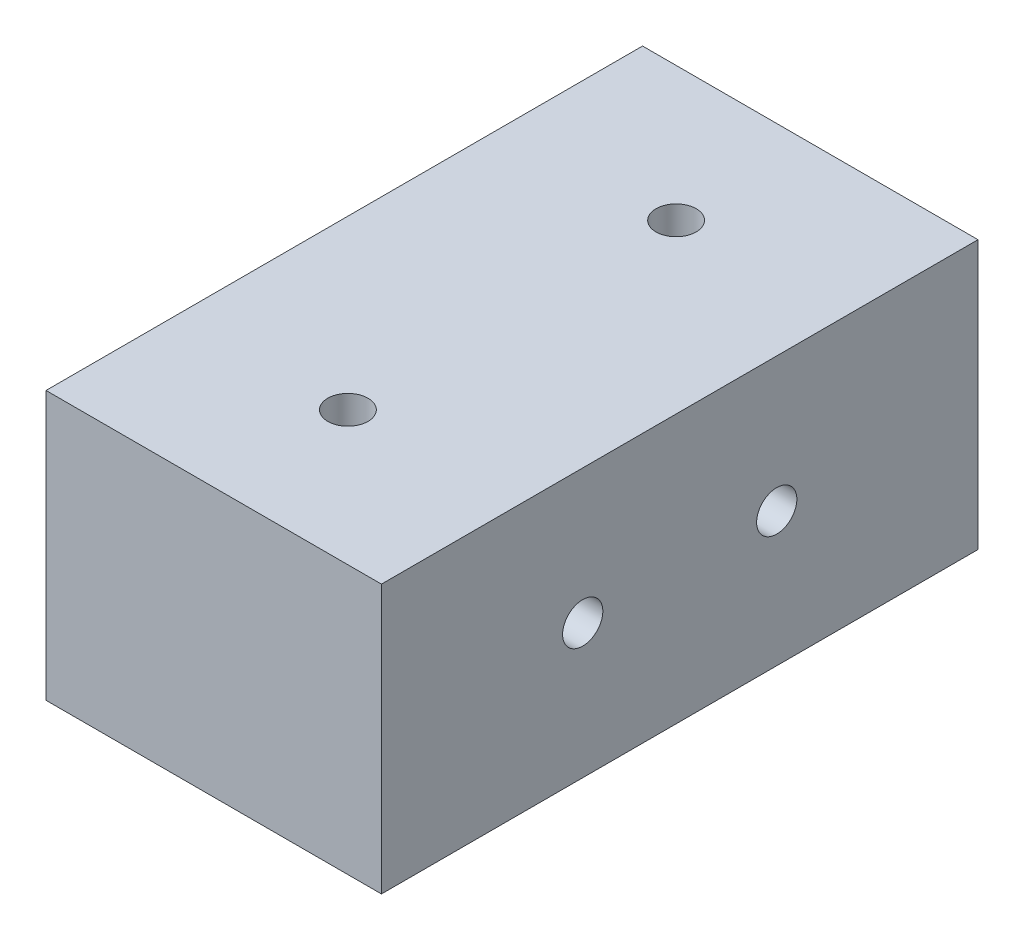
SolidWorks part; units mm, degrees
ref_plane "Alzado" through (0, 0, 0) normal (0, 0, 1) x (1, 0, 0)
ref_plane "Planta" through (0, 0, 0) normal (0, 1, 0) x (1, 0, 0)
ref_plane "Vista lateral" through (0, 0, 0) normal (1, 0, 0) x (0, 0, -1)
sketch "Croquis2" plane through (0, 0, 0) normal (1, 0, 0) x (0, 0, -1)
  line L0 (0, 0) -> (-44.4603, 0)
  line L1 (0, 0) -> (-50, 0) construction
  line L3 (0, -20) -> (-44.4603, -20)
  line L7 (0, -20) -> (0, 0)
  line L8 (-44.4603, -20) -> (-44.4603, 0)
  line L10 (-50, 0) -> (-75.7248, -15.4349) construction
  line L11 (-44.4603, -20) -> (-55.7248, -26.7587) construction
  line L12 (-55.7248, -26.7587) -> (-55.7248, -45.4349) construction
  line L13 (-75.7248, -15.4349) -> (-75.7248, -45.4349) construction
  dimension "D4" = 20
extrude "Saliente-Extruir2" add sketch "Croquis2" along normal blind 25
sketch "Croquis3" plane through (0, -20, 0) normal (0, -1, 0) x (1, 0, 0)
  line L0 (12.5, 0) -> (12.5, 44.4603) construction
  line L1 (25, 0) -> (0, 0) construction
  line L2 (25, 44.4603) -> (0, 44.4603) construction
  circle A0 centre (12.5, 10) radius 1.5
  circle A1 centre (12.5, 34.4603) radius 1.5
  dimension "D1" = 10
  dimension "D3" = 3
  dimension "D4" = 3
  dimension "D2" = 10
extrude "Cortar-Extruir1" cut sketch "Croquis3" against normal through all
sketch "Croquis4" plane through (25, 0, 0) normal (1, 0, 0) x (0, 0, -1)
  line L0 (-44.4603, -10) -> (0, -10) construction
  line L1 (-44.4603, 0) -> (-44.4603, -20) construction
  line L2 (0, -20) -> (0, 0) construction
  circle A0 centre (-29.4603, -10) radius 1.5
  circle A1 centre (-15, -10) radius 1.5
  point P12 (-16.7944, -10)
  dimension "D1" = 15
  dimension "D3" = 3
  dimension "D4" = 3
  dimension "D2" = 15
extrude "Cortar-Extruir2" cut sketch "Croquis4" against normal blind 50
